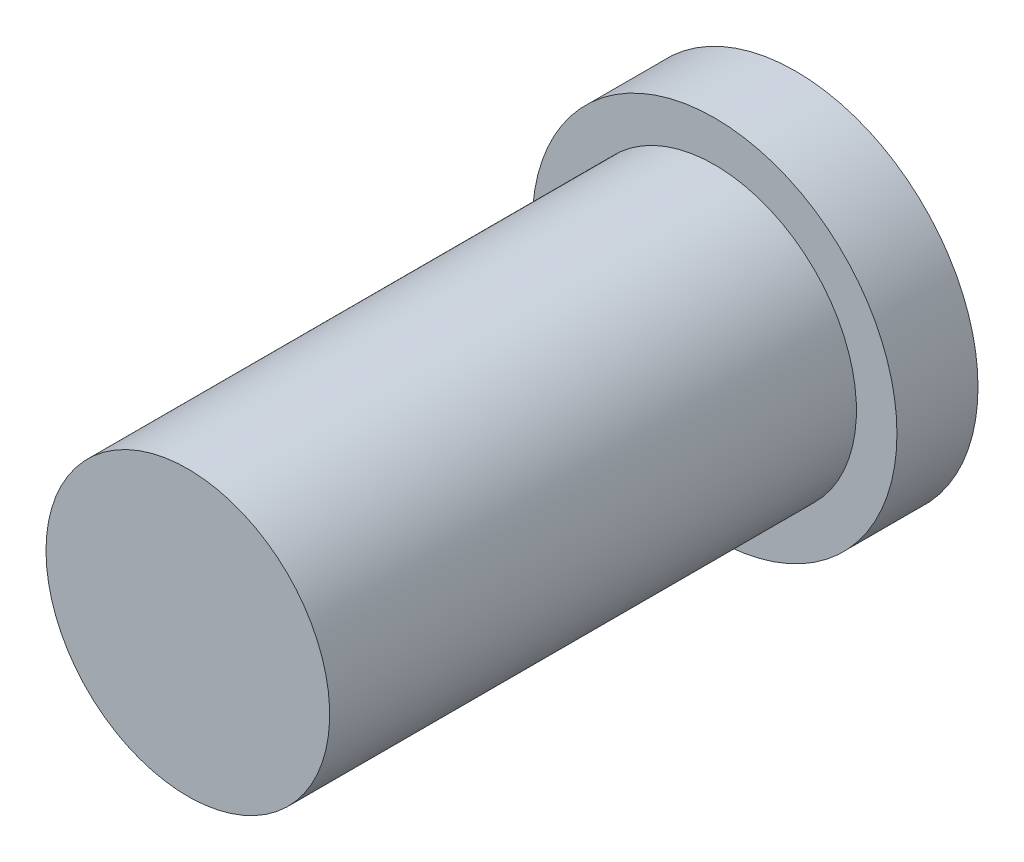
SolidWorks part; units mm, degrees
ref_plane "Ön Düzlem" through (0, 0, 0) normal (0, 0, 1) x (1, 0, 0)
ref_plane "Üst Düzlem" through (0, 0, 0) normal (0, 1, 0) x (1, 0, 0)
ref_plane "Sağ Düzlem" through (0, 0, 0) normal (1, 0, 0) x (0, 0, -1)
sketch "Sketch1" plane through (0, 0, 0) normal (0, 0, 1) x (1, 0, 0)
  circle A0 centre (0, 0) radius 4.5
  dimension "D1" = 9
extrude "Boss-Extrude1" add sketch "Sketch1" along normal blind 2
sketch "Sketch2" plane through (0, 0, 2) normal (0, 0, 1) x (1, 0, 0)
  circle A0 centre (0, 0) radius 3.5
  dimension "D1" = 7
extrude "Boss-Extrude2" add sketch "Sketch2" along normal blind 13
